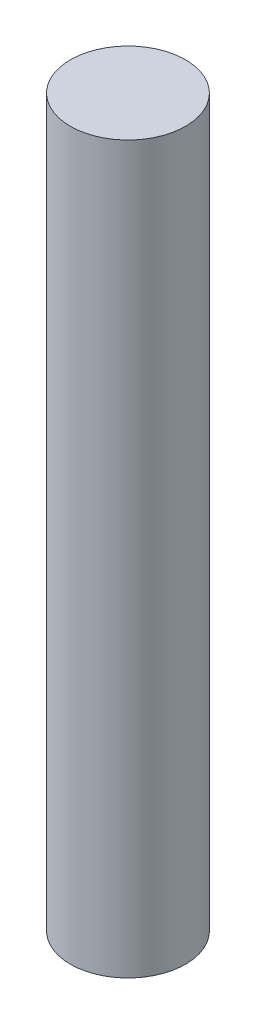
SolidWorks part; units mm, degrees
ref_plane "Front Plane" through (0, 0, 0) normal (0, 0, 1) x (1, 0, 0)
ref_plane "Top Plane" through (0, 0, 0) normal (0, 1, 0) x (1, 0, 0)
ref_plane "Right Plane" through (0, 0, 0) normal (1, 0, 0) x (0, 0, -1)
sketch "Sketch1" plane through (0, 0, 0) normal (0, 1, 0) x (1, 0, 0)
  circle A0 centre (0, 0) radius 6.35
  dimension "D1" = 12.7
extrude "Boss-Extrude1" add sketch "Sketch1" along normal blind 80
